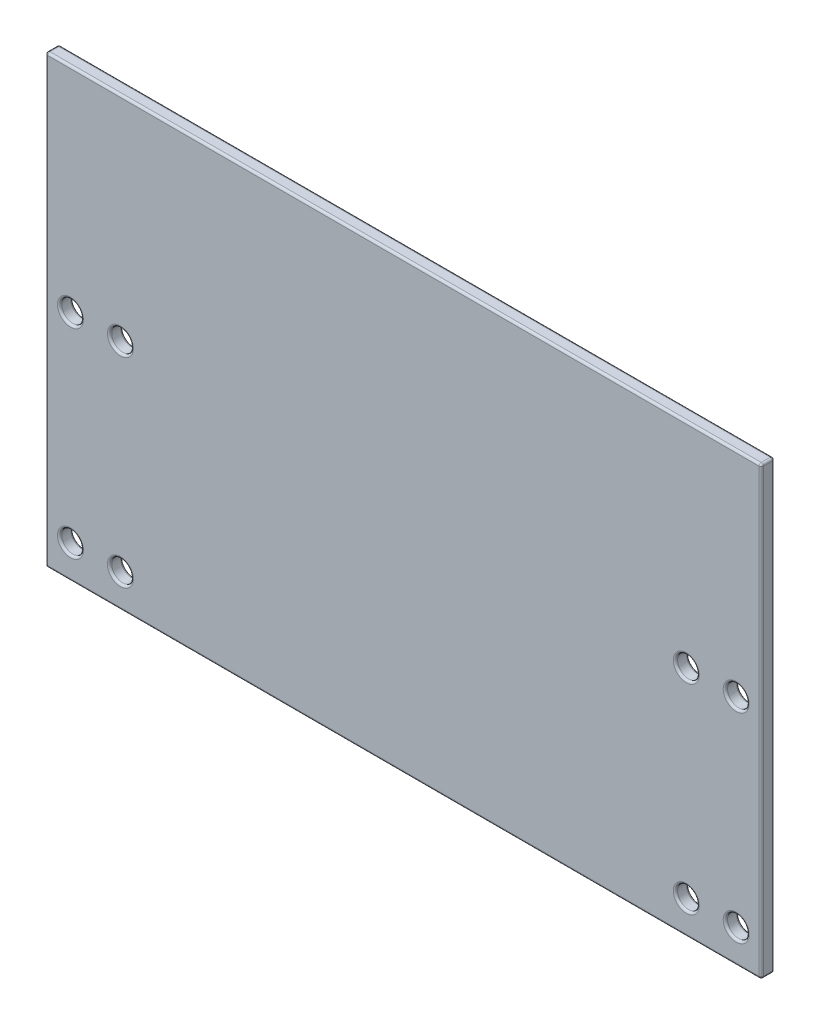
SolidWorks part; units mm, degrees
ref_plane "Alzado" through (0, 0, 0) normal (0, 0, 1) x (1, 0, 0)
ref_plane "Planta" through (0, 0, 0) normal (0, 1, 0) x (1, 0, 0)
ref_plane "Vista lateral" through (0, 0, 0) normal (1, 0, 0) x (0, 0, -1)
sketch "Croquis1" plane through (0, 0, 0) normal (0, 0, 1) x (1, 0, 0)
  line L0 (0, 5) -> (107.5, 5) construction
  line L1 (0, 0) -> (107.5, 0)
  line L2 (0, 0) -> (0, 67)
  line L3 (0, 67) -> (107.5, 67)
  line L4 (107.5, 0) -> (107.5, 67)
  line L5 (3.75, 0) -> (3.75, 67) construction
  line L6 (11.25, 0) -> (11.25, 67) construction
  line L7 (96.25, 67) -> (96.25, 0) construction
  line L8 (103.75, 67) -> (103.75, 0) construction
  line L9 (0, 35) -> (107.5, 35) construction
  circle A0 centre (11.25, 35) radius 1.625
  circle A1 centre (3.75, 35) radius 1.625
  circle A2 centre (11.25, 5) radius 1.625
  circle A3 centre (3.75, 5) radius 1.625
  circle A4 centre (96.25, 35) radius 1.625
  circle A5 centre (103.75, 35) radius 1.625
  circle A6 centre (103.75, 5) radius 1.625
  circle A7 centre (96.25, 5) radius 1.625
  point P33 (0, 0)
  point P34 (0, 0)
  point P35 (0, 0)
  dimension "D9" = 3.25
  dimension "D10" = 3.25
  dimension "D11" = 3.25
  dimension "D12" = 3.25
  dimension "D13" = 3.25
  dimension "D14" = 3.25
  dimension "D15" = 3.25
  dimension "D16" = 3.25
  dimension "D1" = 85
  dimension "D2" = 67
  dimension "D3" = 5
  dimension "D4" = 3.75
  dimension "D5" = 7.5
  dimension "D6" = 7.5
  dimension "D7" = 3.75
  dimension "D8" = 30
extrude "Saliente-Extruir1" add sketch "Croquis1" along normal blind 2
fillet "Redondeo1" radius 0.33 28 edges at (0, 67, 1) (0, 0, 1) (107.5, 0, 1) (107.5, 67, 1) (97.875, 5, 0) (97.875, 35, 0) (12.875, 5, 0) (5.375, 35, 0) (53.75, 0, 0) (107.5, 33.5, 0) (53.75, 67, 0) (0, 33.5, 0) (12.875, 35, 0) (5.375, 5, 0) (105.375, 35, 0) (105.375, 5, 0) (97.875, 5, 2) (105.375, 5, 2) (97.875, 35, 2) (105.375, 35, 2) (12.875, 5, 2) (5.375, 5, 2) (5.375, 35, 2) (12.875, 35, 2) (53.75, 67, 2) (107.5, 33.5, 2) (53.75, 0, 2) (0, 33.5, 2)
